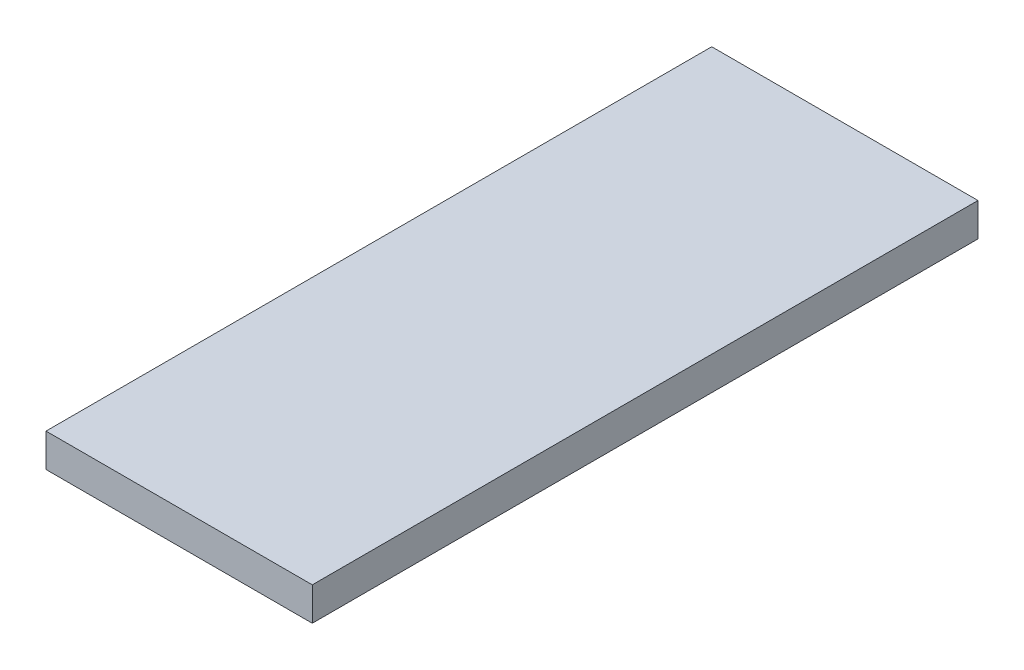
SolidWorks part; units mm, degrees
ref_plane "Front Plane" through (0, 0, 0) normal (0, 0, 1) x (1, 0, 0)
ref_plane "Top Plane" through (0, 0, 0) normal (0, 1, 0) x (1, 0, 0)
ref_plane "Right Plane" through (0, 0, 0) normal (1, 0, 0) x (0, 0, -1)
sketch "Sketch1" plane through (0, 0, 0) normal (0, 1, 0) x (1, 0, 0)
  line L1 (-4, 10) -> (4, 10)
  line L2 (-4, 10) -> (-4, -10)
  line L3 (-4, -10) -> (4, -10)
  line L4 (4, 10) -> (4, -10)
  line L5 (-4, 10) -> (4, -10) construction
  line L6 (-4, -10) -> (4, 10) construction
  point P0 (0, 0)
  dimension "D1" = 20
  dimension "D2" = 8
extrude "Boss-Extrude1" add sketch "Sketch1" along normal blind 1
